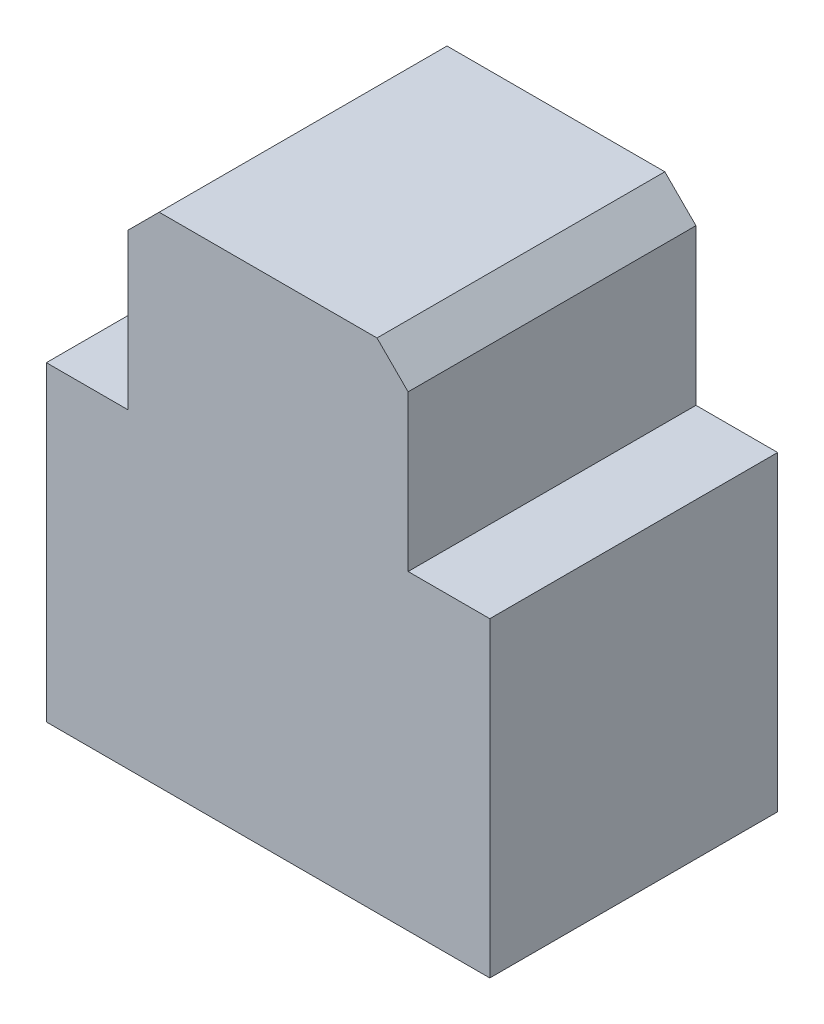
SolidWorks part; units mm, degrees
ref_plane "Front Plane" through (0, 0, 0) normal (0, 0, 1) x (1, 0, 0)
ref_plane "Top Plane" through (0, 0, 0) normal (0, 1, 0) x (1, 0, 0)
ref_plane "Right Plane" through (0, 0, 0) normal (1, 0, 0) x (0, 0, -1)
sketch "Sketch1" plane through (0, 0, 0) normal (0, 0, 1) x (1, 0, 0)
  line L0 (0, 4.4) -> (0, 0) construction
  line L7 (-2.85, 2) -> (2.85, 2)
  line L8 (-2.85, 2) -> (-2.85, -2)
  line L9 (-2.85, -2) -> (2.85, -2)
  line L10 (2.85, 2) -> (2.85, -2)
  line L11 (-2.85, 2) -> (2.85, -2) construction
  line L12 (-2.85, -2) -> (2.85, 2) construction
  line L13 (-1.8, 2) -> (1.8, 2)
  line L14 (-1.8, 2) -> (-1.8, 4.4)
  line L15 (-1.8, 4.4) -> (1.8, 4.4)
  line L16 (1.8, 2) -> (1.8, 4.4)
  point P0 (0, 0)
  point P6 (0, 0)
  dimension "D1" = 5.7
  dimension "D3" = 4
  dimension "D5" = 3.6
  dimension "D6" = 2.4
extrude "Boss-Extrude1" add sketch "Sketch1" along normal blind 3.7 contours L10 L7 L8 L9 | L7 L16 L15 L14
chamfer "Chamfer1" distance 0.4 angle 45 2 edges at (-1.8, 4.4, 1.85) (1.8, 4.4, 1.85)
